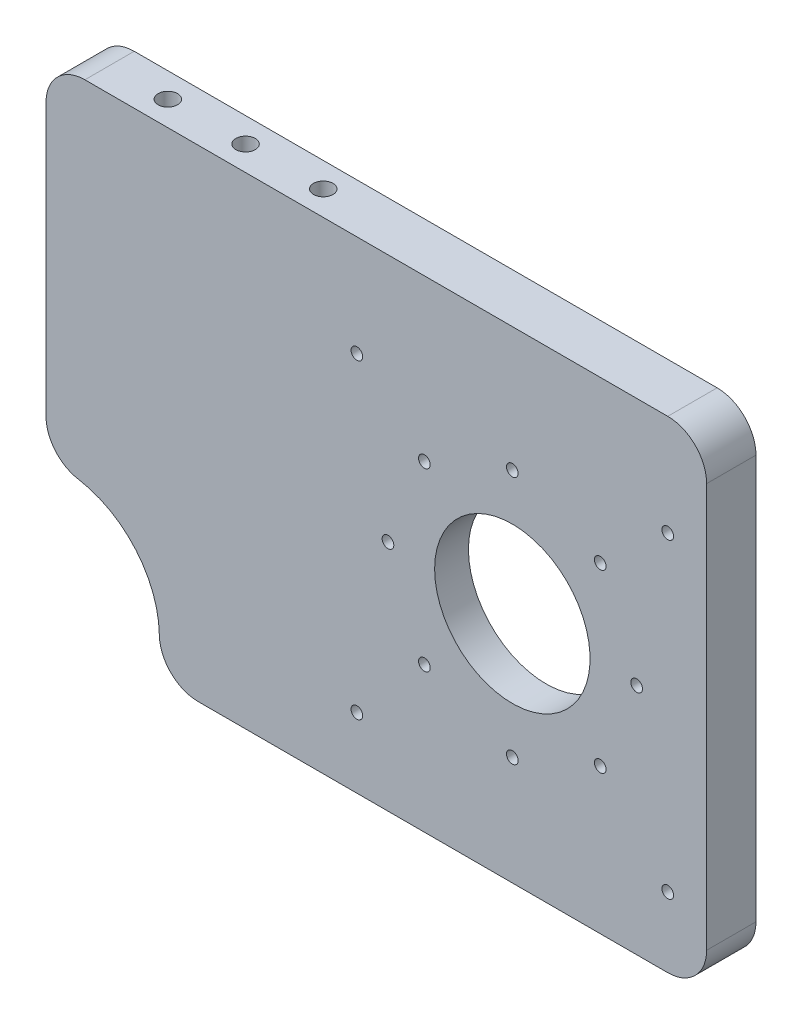
SolidWorks part; units mm, degrees
ref_plane "Front Plane" through (0, 0, 0) normal (0, 0, 1) x (1, 0, 0)
ref_plane "Top Plane" through (0, 0, 0) normal (0, 1, 0) x (1, 0, 0)
ref_plane "Right Plane" through (0, 0, 0) normal (1, 0, 0) x (0, 0, -1)
sketch "Croquis1" plane through (0, 0, 0) normal (0, 0, 1) x (1, 0, 0)
  line L0 (-106.744, 74.6976) -> (43.256, 74.6976)
  line L1 (-77.581, -49.3024) -> (-46.744, -49.3024)
  line L2 (-116.744, -5.3024) -> (-116.744, 64.6976)
  line L3 (-46.744, -49.3024) -> (43.256, -49.3024)
  line L4 (53.256, -39.3024) -> (53.256, 40.6976)
  line L5 (53.256, 64.6976) -> (53.256, 40.6976)
  arc A0 (-87.58, -39.4483) -> (-108.4106, -15.1625) centre (-112.5773, -39.8129) ccw
  arc A1 (43.256, -49.3024) -> (53.256, -39.3024) centre (43.256, -39.3024) ccw
  arc A2 (-77.581, -49.3024) -> (-87.58, -39.4483) centre (-77.581, -39.3024) cw
  arc A3 (-116.744, -5.3024) -> (-108.4106, -15.1625) centre (-106.744, -5.3024) ccw
  arc A4 (-116.744, 64.6976) -> (-106.744, 74.6976) centre (-106.744, 64.6976) cw
  arc A5 (43.256, 74.6976) -> (53.256, 64.6976) centre (43.256, 64.6976) cw
  dimension "D3" = 25
  dimension "D5" = 10
  dimension "D6" = 10
  dimension "D1" = 80
  dimension "D2" = 90
  dimension "D4" = 170
  dimension "D7" = 124
  dimension "D8" = 70
extrude "Saliente-Extruir1" add sketch "Croquis1" along normal blind 12.7
sketch "Croquis2" plane through (0, 0, 0) normal (0, 0, -1) x (-1, 0, 0)
  line L0 (-53.256, -39.3024) -> (-53.256, 64.6976) construction
  line L1 (77.581, -49.3024) -> (-43.256, -49.3024) construction
  circle A0 centre (-3.256, 10.6976) radius 20
  dimension "D1" = 50
  dimension "D2" = 60
extrude "Cortar-Extruir1" cut sketch "Croquis2" against normal blind 12.7
sketch "Croquis4" plane through (0, 0, 0) normal (0, 0, -1) x (-1, 0, 0)
  line L0 (-53.256, -39.3024) -> (-53.256, 64.6976) construction
  line L1 (-43.256, 74.6976) -> (106.744, 74.6976) construction
  circle A0 centre (36.744, 48.6976) radius 3
  circle A1 centre (-43.256, 48.6976) radius 3
  circle A2 centre (36.744, -31.3024) radius 3
  circle A3 centre (-43.256, -31.3024) radius 3
  dimension "D1" = 80
  dimension "D2" = 80
  dimension "D3" = 80
  dimension "D4" = 80
  dimension "D5" = 10
  dimension "D6" = 26
extrude "Cortar-Extruir3" cut sketch "Croquis4" against normal blind 3
sketch "Croquis5" plane through (0, 0, 0) normal (0, 0, -1) x (-1, 0, 0)
  circle A0 centre (-3.256, 10.6976) radius 35
extrude "Cortar-Extruir4" cut sketch "Croquis5" against normal blind 4
sketch "Croquis6" plane through (0, 0, 4) normal (0, 0, -1) x (-1, 0, 0)
  circle A1 centre (-3.256, 42.6976) radius 1.5
  circle A2 centre (19.3714, 33.325) radius 1.5
  circle A3 centre (28.744, 10.6976) radius 1.5
  circle A4 centre (19.3714, -11.9298) radius 1.5
  circle A5 centre (-3.256, -21.3024) radius 1.5
  circle A6 centre (-25.8834, -11.9298) radius 1.5
  circle A7 centre (-35.256, 10.6976) radius 1.5
  circle A8 centre (-25.8834, 33.325) radius 1.5
  point P2 (-3.256, 10.6976)
  point P20 (-3.256, 10.6976)
  dimension "D2" = 32
extrude "Cortar-Extruir5" cut sketch "Croquis6" against normal blind 22
sketch "Croquis7" plane through (0, 0, 4) normal (0, 0, -1) x (-1, 0, 0)
  circle A0 centre (-3.256, 10.6976) radius 35
extrude "Cortar-Extruir6" cut sketch "Croquis7" along normal blind 10 draft 45 draft outward yes
sketch "Croquis8" plane through (0, 0, 0) normal (0, 0, -1) x (-1, 0, 0)
  circle A0 centre (-43.256, 48.6976) radius 1.5
  circle A1 centre (36.744, 48.6976) radius 1.5
  circle A2 centre (36.744, -31.3024) radius 1.5
  circle A3 centre (-43.256, -31.3024) radius 1.5
extrude "Cortar-Extruir7" cut sketch "Croquis8" against normal blind 29
sketch "Croquis9" plane through (0, 74.6976, 0) normal (0, 1, 0) x (1, 0, 0)
  line L0 (-106.744, -12.7) -> (-106.744, 0) construction
  line L1 (43.256, -12.7) -> (-106.744, -12.7) construction
  circle A0 centre (-91.744, -6.35) radius 2.5
  circle A1 centre (-71.744, -6.35) radius 2.5
  circle A2 centre (-51.744, -6.35) radius 2.5
  dimension "D1" = 15
  dimension "D3" = 6.35
  dimension "D2" = 3
extrude "Cortar-Extruir8" cut sketch "Croquis9" against normal blind 20
sketch "Croquis10" plane through (-116.744, 0, 0) normal (-1, 0, 0) x (0, 0, 1)
  line L0 (12.7, 64.6976) -> (0, 64.6976) construction
  line L1 (12.7, 64.6976) -> (12.7, -5.3024) construction
  circle A0 centre (6.35, 49.6976) radius 2.5
  circle A1 centre (6.35, 29.6976) radius 2.5
  circle A2 centre (6.35, 9.6976) radius 2.5
  dimension "D1" = 15
  dimension "D2" = 6.35
  dimension "D3" = 3
extrude "Cortar-Extruir9" cut sketch "Croquis10" against normal blind 20
